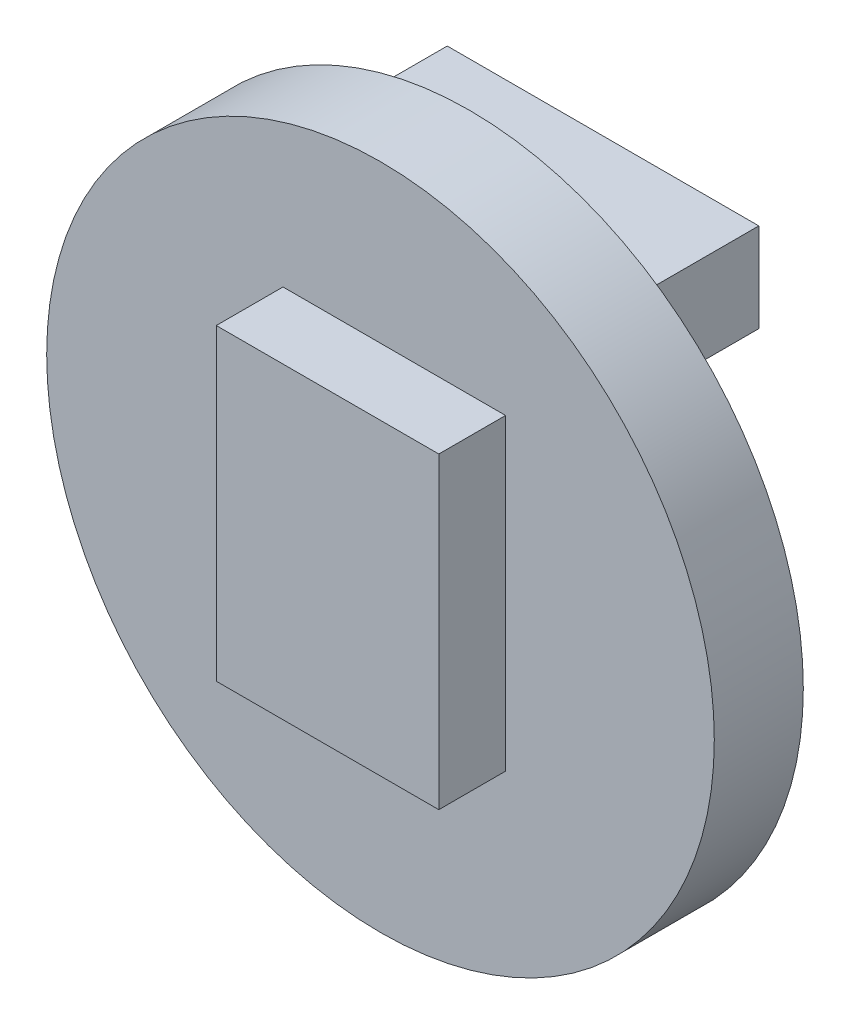
SolidWorks part; units mm, degrees
ref_plane "Front Plane" through (0, 0, 0) normal (0, 0, 1) x (1, 0, 0)
ref_plane "Top Plane" through (0, 0, 0) normal (0, 1, 0) x (1, 0, 0)
ref_plane "Right Plane" through (0, 0, 0) normal (1, 0, 0) x (0, 0, -1)
sketch "Sketch1" plane through (0, 0, 0) normal (0, 0, 1) x (1, 0, 0)
  circle A0 centre (0, 0) radius 7.5
  dimension "D1" = 15
extrude "Boss-Extrude1" add sketch "Sketch1" along normal blind 2
sketch "Sketch2" plane through (0, 0, 2) normal (0, 0, 1) x (1, 0, 0)
  line L1 (-2.1898, 3.9665) -> (2.8102, 3.9665)
  line L2 (-2.1898, 3.9665) -> (-2.1898, -2.9543)
  line L3 (-2.1898, -2.9543) -> (2.8102, -2.9543)
  line L4 (2.8102, 3.9665) -> (2.8102, -2.9543)
  line L5 (-2.1898, 3.9665) -> (2.8102, -2.9543) construction
  line L6 (-2.1898, -2.9543) -> (2.8102, 3.9665) construction
  point P0 (0.3102, 0.5061)
  dimension "D1" = 6.9208
  dimension "D2" = 5
extrude "Boss-Extrude2" add sketch "Sketch2" along normal blind 1.5
sketch "Sketch3" plane through (0, 0, 0) normal (0, 0, -1) x (-1, 0, 0)
  line L1 (-3.5, 5.5) -> (3.5, 5.5)
  line L2 (-3.5, 5.5) -> (-3.5, 3.5)
  line L3 (-3.5, 3.5) -> (3.5, 3.5)
  line L4 (3.5, 5.5) -> (3.5, 3.5)
  line L5 (-3.5, 5.5) -> (3.5, 3.5) construction
  line L6 (-3.5, 3.5) -> (3.5, 5.5) construction
  circle A0 centre (0, 0) radius 7.5 construction
  point P0 (0, 4.5)
  point P5 (0, 7.5)
  dimension "D1" = 2
  dimension "D2" = 7
  dimension "D3" = 2
extrude "Boss-Extrude3" add sketch "Sketch3" along normal blind 3
